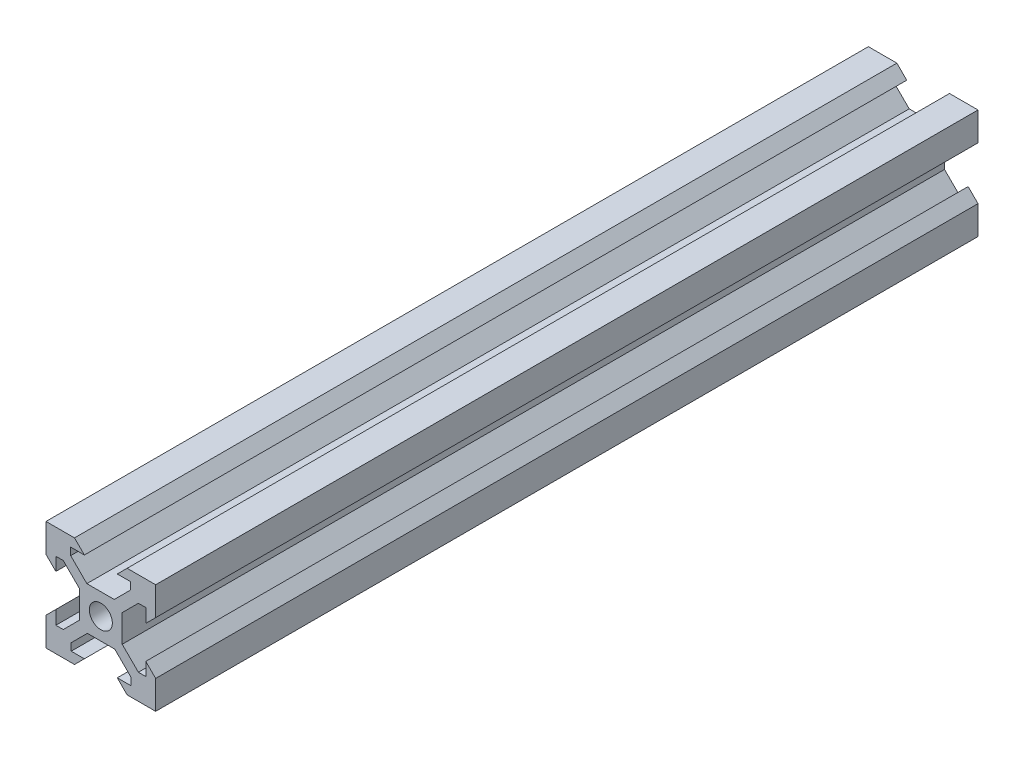
SolidWorks part; units mm, degrees
ref_plane "Alzado" through (0, 0, 0) normal (0, 0, 1) x (1, 0, 0)
ref_plane "Planta" through (0, 0, 0) normal (0, 1, 0) x (1, 0, 0)
ref_plane "Vista lateral" through (0, 0, 0) normal (1, 0, 0) x (0, 0, -1)
sketch "Croquis1" plane through (0, 0, 0) normal (0, 0, 1) x (1, 0, 0)
  line L0 (0, 20.9127) -> (0, 3.9) construction
  line L1 (-24.1207, 0) -> (-3.9, 0) construction
  line L2 (3, 8.2) -> (5.4, 8.2)
  line L3 (-10, 10) -> (-4.8, 10)
  line L4 (8.2, -3) -> (8.2, -5.4)
  line L5 (10, 10) -> (10, 4.8)
  line L6 (3.9, 2.55) -> (3.9, -2.45)
  line L7 (8.2, 5.5) -> (8.2, 3)
  line L8 (-2.55, 3.9) -> (2.45, 3.9)
  line L9 (8.2, 5.5) -> (6.85, 5.5)
  line L10 (8.2, -5.4) -> (6.85, -5.4)
  line L11 (8.2, -3) -> (10, -4.8)
  line L12 (-5.5, 8.2) -> (-3, 8.2)
  line L13 (-5.5, 8.2) -> (-5.5, 6.85)
  line L14 (10, -10) -> (10, -4.8)
  line L15 (5.4, 8.2) -> (5.4, 6.85)
  line L16 (3, 8.2) -> (4.8, 10)
  line L17 (10, 10) -> (4.8, 10)
  line L18 (8.2, 3) -> (10, 4.8)
  line L19 (6.85, 5.5) -> (3.9, 2.55)
  line L20 (6.85, -5.4) -> (3.9, -2.45)
  line L21 (20.9127, 0) -> (3.9, 0) construction
  line L22 (-3, -8.2) -> (-5.4, -8.2)
  line L23 (10, -10) -> (4.8, -10)
  line L24 (2.55, -3.9) -> (-2.45, -3.9)
  line L25 (5.5, -8.2) -> (3, -8.2)
  line L26 (5.5, -8.2) -> (5.5, -6.85)
  line L27 (-5.4, -8.2) -> (-5.4, -6.85)
  line L28 (-3, -8.2) -> (-4.8, -10)
  line L29 (-10, -10) -> (-4.8, -10)
  line L30 (3, -8.2) -> (4.8, -10)
  line L31 (5.5, -6.85) -> (2.55, -3.9)
  line L32 (-5.4, -6.85) -> (-2.45, -3.9)
  line L33 (0, -20.9127) -> (0, -3.9) construction
  line L34 (-8.2, 3) -> (-8.2, 5.4)
  line L35 (-10, -10) -> (-10, -4.8)
  line L36 (-3.9, -2.55) -> (-3.9, 2.45)
  line L37 (-8.2, -5.5) -> (-8.2, -3)
  line L38 (-8.2, -5.5) -> (-6.85, -5.5)
  line L39 (-8.2, 5.4) -> (-6.85, 5.4)
  line L40 (-3, 8.2) -> (-4.8, 10)
  line L41 (-8.2, 3) -> (-10, 4.8)
  line L42 (-5.5, 6.85) -> (-2.55, 3.9)
  line L43 (-10, 10) -> (-10, 4.8)
  line L44 (5.4, 6.85) -> (2.45, 3.9)
  line L45 (-8.2, -3) -> (-10, -4.8)
  line L46 (-6.85, -5.5) -> (-3.9, -2.55)
  line L47 (-6.85, 5.4) -> (-3.9, 2.45)
  line L48 (-20.9127, 0) -> (-3.9, 0) construction
  circle A0 centre (0, 0) radius 2.1
  point P45 (-0.05, 0.05)
  point P64 (0, 0)
  dimension "D5" = 4
  dimension "D1" = 45
  dimension "D2" = 45
  dimension "D3" = 6
  dimension "D4" = 3
  dimension "D6" = 8.2
extrude "Saliente-Extruir1" add sketch "Croquis1" along normal blind 150
